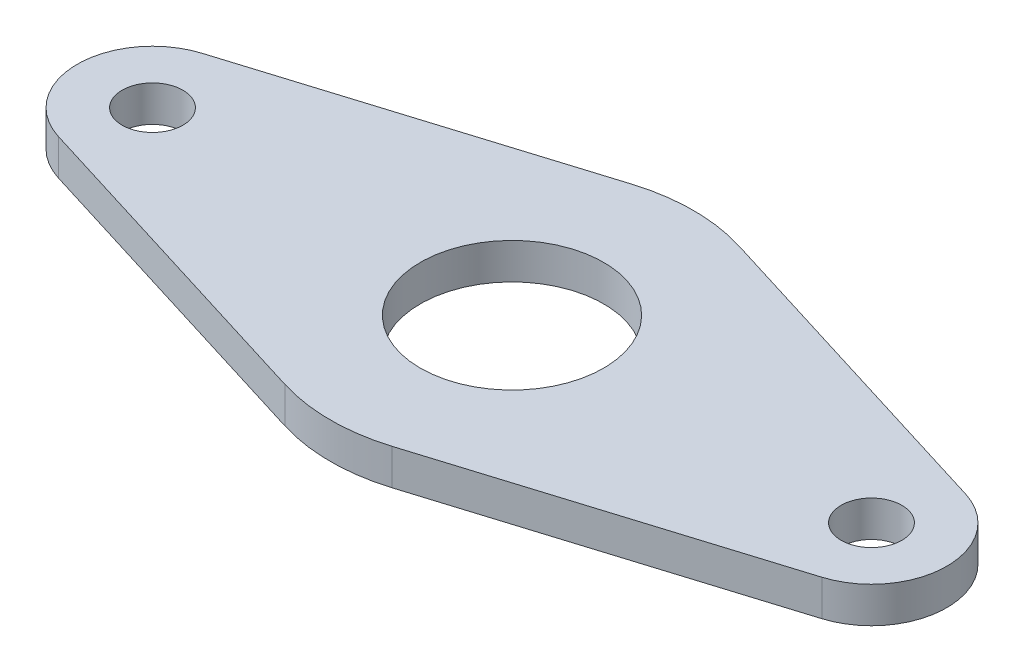
SolidWorks part; units mm, degrees
ref_plane "Front" through (0, 0, 0) normal (0, 0, 1) x (1, 0, 0)
ref_plane "Top" through (0, 0, 0) normal (0, 1, 0) x (1, 0, 0)
ref_plane "Right" through (0, 0, 0) normal (1, 0, 0) x (0, 0, -1)
sketch "Sketch1" plane through (0, 0, 0) normal (0, 1, 0) x (1, 0, 0)
  line L0 (25.4, 0) -> (-25.4, 0) construction
  line L1 (-26.9724, 5.0837) -> (-3.7904, 12.2542)
  line L2 (-26.9724, -5.0837) -> (-3.7904, -12.2542)
  line L3 (3.7904, 12.2542) -> (26.9724, 5.0837)
  line L4 (26.9724, -5.0837) -> (3.7904, -12.2542)
  line L5 (-25.4, 5.3213) -> (-25.4, 2.1463) construction
  line L7 (0, 6.477) -> (0, 12.827) construction
  line L9 (25.4, 5.3213) -> (25.4, 2.1463) construction
  circle A0 centre (0, 0) radius 6.477
  circle A1 centre (-25.4, 0) radius 2.1463
  circle A2 centre (25.4, 0) radius 2.1463
  circle A3 centre (-25.4, 0) radius 5.3213
  circle A4 centre (0, 0) radius 12.827
  circle A5 centre (25.4, 0) radius 5.3213
  point P6 (0, 0)
  dimension "D1" = 4.2926
  dimension "D2" = 12.954
  dimension "D4" = 3.175
  dimension "D5" = 6.35
  dimension "D3" = 50.8
extrude "Boss-Extrude1" add sketch "Sketch1" along normal blind 2.54 contours A4 L1 A3 L2 | A3 A1 | A4 A0 | A5 L3 A4 L4 | A5 A2
